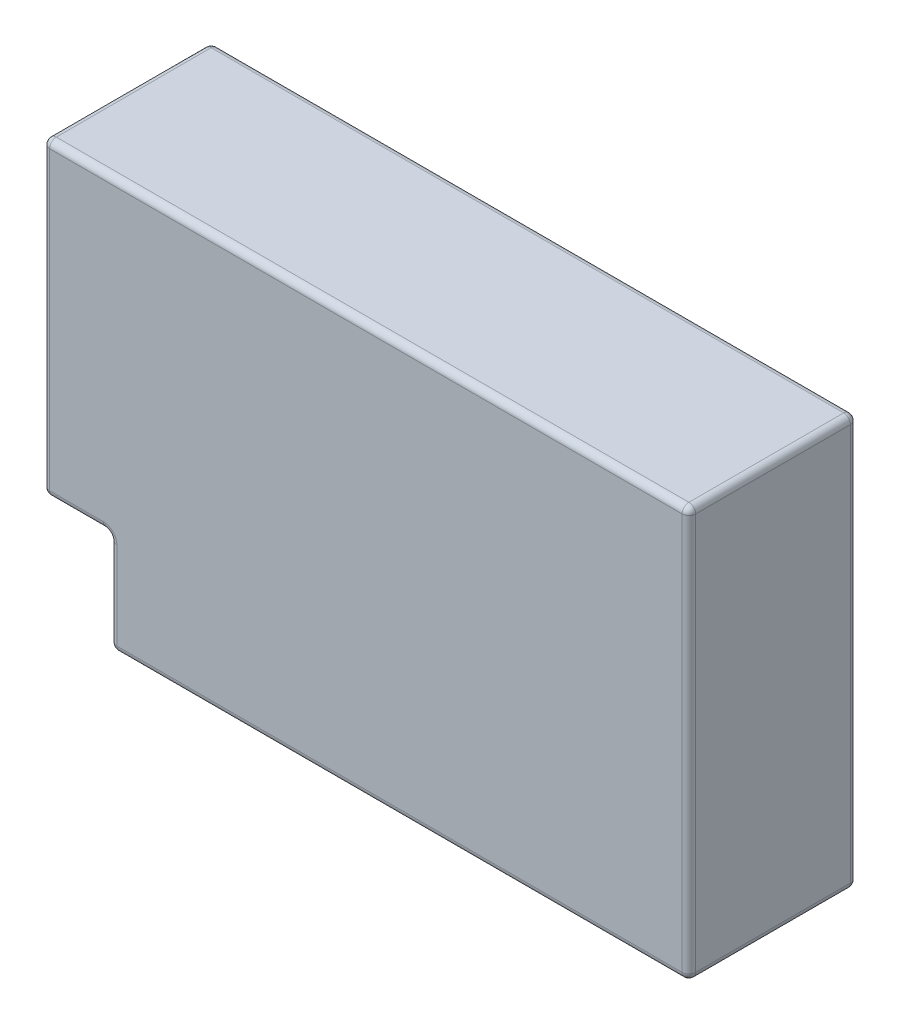
SolidWorks part; units mm, degrees
ref_plane "Płaszczyzna przednia" through (0, 0, 0) normal (0, 0, 1) x (1, 0, 0)
ref_plane "Płaszczyzna górna" through (0, 0, 0) normal (0, 1, 0) x (1, 0, 0)
ref_plane "Płaszczyzna prawa" through (0, 0, 0) normal (1, 0, 0) x (0, 0, -1)
sketch "Szkic1" plane through (0, 0, 0) normal (0, 0, 1) x (1, 0, 0)
  line L0 (-34.4784, 29.894) -> (-34.4784, -16.106)
  line L1 (-34.4784, 29.894) -> (61.5216, 29.894)
  line L2 (-24.4784, -31.106) -> (61.5216, -31.106)
  line L4 (61.5216, 29.894) -> (61.5216, -31.106)
  line L7 (-34.4784, -16.106) -> (-24.4784, -16.106)
  line L8 (-24.4784, -31.106) -> (-24.4784, -16.106)
  dimension "D1" = 96
  dimension "D3" = 10
  dimension "D4" = 15
extrude "Dodanie-wyciągnięcie1" add sketch "Szkic1" along normal blind 25
fillet "Zaokrąglenie3" radius 1 18 edges at (-34.4784, 29.894, 12.5) (-34.4784, -16.106, 12.5) (-24.4784, -16.106, 12.5) (-24.4784, -31.106, 12.5) (61.5216, -31.106, 12.5) (61.5216, 29.894, 12.5) (61.5216, -0.606, 25) (18.5216, -31.106, 25) (-24.4784, -23.606, 25) (-29.4784, -16.106, 25) (-34.4784, 6.894, 25) (13.5216, 29.894, 25) (-34.4784, 6.894, 0) (-29.4784, -16.106, 0) (-24.4784, -23.606, 0) (18.5216, -31.106, 0) (61.5216, -0.606, 0) (13.5216, 29.894, 0)
